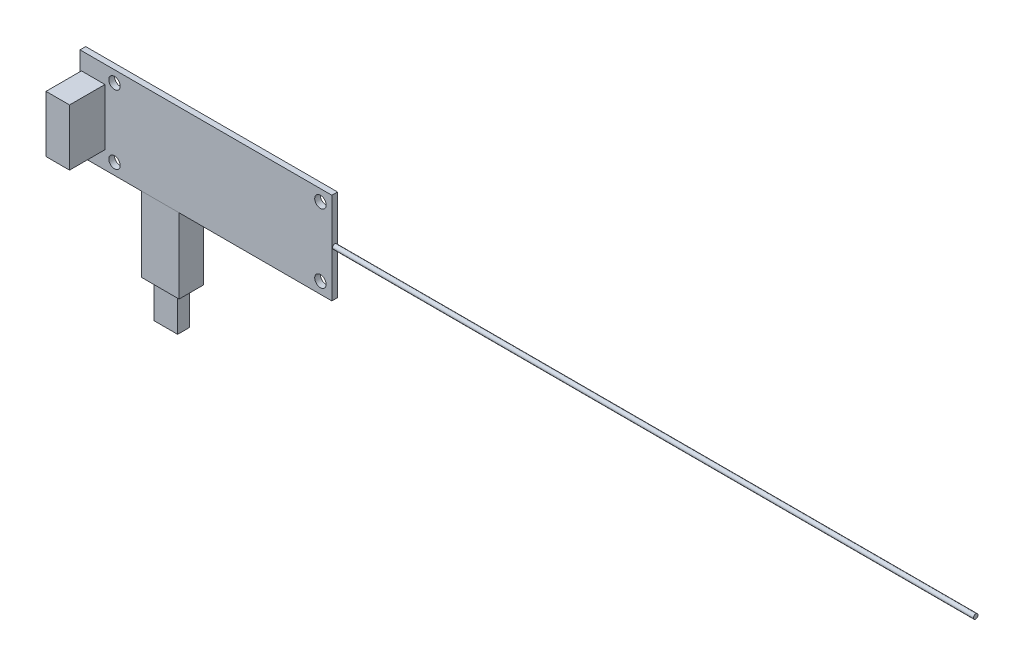
SolidWorks part; units mm, degrees
material "Printed Circuit Board"
ref_plane "Front Plane" through (0, 0, 0) normal (0, 0, 1) x (1, 0, 0)
ref_plane "Top Plane" through (0, 0, 0) normal (0, 1, 0) x (1, 0, 0)
ref_plane "Right Plane" through (0, 0, 0) normal (1, 0, 0) x (0, 0, -1)
sketch "Sketch1" plane through (0, 0, 0) normal (0, 0, 1) x (1, 0, 0)
  line L1 (-34.925, -12.7) -> (34.925, -12.7)
  line L2 (-34.925, -12.7) -> (-34.925, 12.7)
  line L3 (-34.925, 12.7) -> (34.925, 12.7)
  line L4 (34.925, -12.7) -> (34.925, 12.7)
  line L5 (-34.925, -12.7) -> (34.925, 12.7) construction
  line L6 (-34.925, 12.7) -> (34.925, -12.7) construction
  point P0 (0, 0)
  dimension "D1" = 69.85
  dimension "D2" = 25.4
extrude "Extrude1" add sketch "Sketch1" along normal blind 1.5748
sketch "Sketch2" plane through (0, 0, 1.5748) normal (0, 0, 1) x (1, 0, 0)
  line L0 (-34.925, 9.525) -> (-25.3822, 9.525) construction
  line L1 (-34.925, 12.7) -> (-34.925, -12.7) construction
  line L2 (-25.3822, 9.525) -> (31.75, 9.525) construction
  dimension "D1" = 9.5428
  dimension "D2" = 66.675
  dimension "D3" = 3.175
hole_wizard "1/8 (0.125) Diameter Hole1" positions "3DSketch1" profile "Sketch3" hole size "1/8" standard "Ansi Inch"
sketch3d "3DSketch1"
  point P0 (-25.3822, 9.525, 1.5748)
  point P3 (31.75, 9.525, 1.5748)
sketch "Sketch3" plane through (-25.3822, 9.525, 1.5748) normal (1, 0, 0) x (0, -1, 0)
  line L0 (0, 0) -> (0, 16.9559)
  line L1 (0, 16.9559) -> (1.5875, 16.002)
  line L2 (1.5875, 16.002) -> (1.5875, 0)
  line L5 (1.5875, 0) -> (0, 0)
  line L10 (0, 16.9559) -> (-1.5875, 16.002) construction
  line L11 (0, -6.35) -> (0, 107.95) construction
  dimension "Hole Dia." = 3.175
  dimension "Hole Depth" = 16.002
  dimension "Drill Angle" = 118
mirror "Mirror1" about plane through (0, 0, 0) normal (0, 1, 0) of "1/8 (0.125) Diameter Hole1"
sketch "Sketch4" plane through (34.925, 0, 0) normal (1, 0, 0) x (0, 0, -1)
  line L0 (0, 0) -> (-1.5441, 0) construction
  line L1 (0, -12.7) -> (0, 12.7) construction
  circle A0 centre (-0.772, 0) radius 0.635
  dimension "D1" = 1.27
extrude "Boss-Extrude1" add sketch "Sketch4" along normal blind 177.8
sketch "Sketch5" plane through (0, 0, 0) normal (0, 0, -1) x (-1, 0, 0)
  line L0 (34.925, -12.7) -> (-34.925, -12.7) construction
  line L1 (17.1361, -12.7) -> (9.0081, -12.7)
  line L2 (17.1361, -12.7) -> (17.1361, -3.9624)
  line L3 (17.1361, -3.9624) -> (9.0081, -3.9624)
  line L4 (9.0081, -12.7) -> (9.0081, -3.9624)
  dimension "D1" = 8.7376
  dimension "D2" = 8.128
extrude "USB Connector" add sketch "Sketch5" along normal blind 4.1402
sketch "Sketch6" plane through (0, -12.7, 0) normal (0, -1, 0) x (1, 0, 0)
  line L1 (-17.9544, 1.4835) -> (-7.548, 1.4835)
  line L2 (-17.9544, 1.4835) -> (-17.9544, -5.2984)
  line L3 (-17.9544, -5.2984) -> (-7.548, -5.2984)
  line L4 (-7.548, 1.4835) -> (-7.548, -5.2984)
  line L5 (-17.9544, 1.4835) -> (-7.548, -5.2984) construction
  line L6 (-17.9544, -5.2984) -> (-7.548, 1.4835) construction
  point P0 (-12.7512, -1.9075)
extrude "Charger" add sketch "Sketch6" along normal blind 20.828
sketch "Sketch7" plane through (0, -33.528, 0) normal (0, -1, 0) x (1, 0, 0)
  line L1 (-16.0158, 0) -> (-9.4301, 0)
  line L2 (-16.0158, 0) -> (-16.0158, -3.2572)
  line L3 (-16.0158, -3.2572) -> (-9.4301, -3.2572)
  line L4 (-9.4301, 0) -> (-9.4301, -3.2572)
  line L5 (-16.0158, 0) -> (-9.4301, -3.2572) construction
  line L6 (-16.0158, -3.2572) -> (-9.4301, 0) construction
  point P0 (-12.723, -1.6286)
extrude "Boss-Extrude2" add sketch "Sketch7" along normal blind 10.16
sketch "Sketch8" plane through (0, 0, 1.5748) normal (0, 0, 1) x (1, 0, 0)
  line L0 (0, 0) -> (-31.2801, 0) construction
  line L1 (-34.544, 7.8359) -> (-28.0162, 7.8359)
  line L2 (-34.544, 7.8359) -> (-34.544, -7.8359)
  line L3 (-34.544, -7.8359) -> (-28.0162, -7.8359)
  line L4 (-28.0162, 7.8359) -> (-28.0162, -7.8359)
  line L5 (-34.544, 7.8359) -> (-28.0162, -7.8359) construction
  line L6 (-34.544, -7.8359) -> (-28.0162, 7.8359) construction
  line L7 (-34.925, 12.7) -> (-34.925, -12.7) construction
  point P0 (-31.2801, 0)
  dimension "D1" = 6.5278
  dimension "D2" = 15.6718
  dimension "D3" = 0.381
extrude "Boss-Extrude3" add sketch "Sketch8" along normal blind 9.8298
